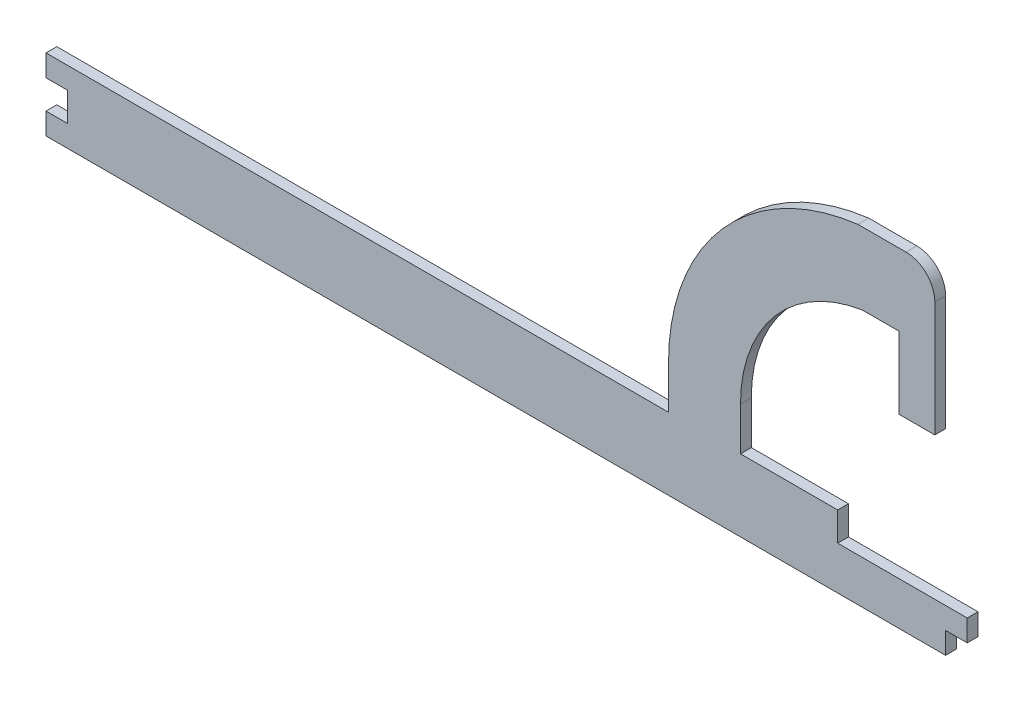
SolidWorks part; units mm, degrees
ref_plane "Спереди" through (0, 0, 0) normal (0, 0, 1) x (1, 0, 0)
ref_plane "Сверху" through (0, 0, 0) normal (0, 1, 0) x (1, 0, 0)
ref_plane "Справа" through (0, 0, 0) normal (1, 0, 0) x (0, 0, -1)
sketch "Эскиз2" plane through (0, 0, 0) normal (0, 0, 1) x (1, 0, 0)
  line L1 (0, 0) -> (244, 0)
  line L2 (0, 0) -> (0, 20) construction
  line L18 (244, 12) -> (244, 0) construction
  line L33 (0, 20) -> (167, 20)
  line L35 (187, 20) -> (187, 32)
  line L36 (187, 32) -> (167, 32) construction
  line L37 (167, 32) -> (167, 20)
  line L38 (231, 71.5474) -> (231, 51.5474)
  line L39 (231, 51.5474) -> (241, 51.5474)
  line L42 (187, 20) -> (214, 20)
  line L44 (241, 83.5474) -> (241, 51.5474)
  line L45 (231, 71.5474) -> (221, 71.5474)
  line L46 (233, 91.5474) -> (219.6446, 91.5474)
  line L47 (214, 20) -> (214, 12)
  line L48 (214, 12) -> (244, 12)
  line L49 (0, 20) -> (-6, 20)
  line L50 (-6, 20) -> (-6, 14)
  line L51 (-6, 14) -> (0, 14)
  line L52 (0, 14) -> (0, 6)
  line L53 (0, 6) -> (-6, 6)
  line L54 (-6, 6) -> (-6, 0)
  line L55 (-6, 0) -> (0, 0)
  line L56 (244, 12) -> (250, 12)
  line L57 (250, 12) -> (250, 6)
  line L58 (250, 6) -> (244, 6)
  line L59 (244, 6) -> (244, 0)
  arc A2 (241, 83.5474) -> (233, 91.5474) centre (233, 83.5474) ccw
  arc A7 (221, 71.5474) -> (187, 32) centre (227, 32) ccw
  arc A8 (219.6446, 91.5474) -> (167, 32) centre (227, 32) ccw
  dimension "D3" = 12
  dimension "D4" = 20
  dimension "D5" = 10
  dimension "D8" = 80
  dimension "D9" = 20
  dimension "D1" = 244
  dimension "D2" = 20
  dimension "D6" = 3
  dimension "D7" = 10
  dimension "D10" = 20
  dimension "D11" = 8
  dimension "D12" = 17
  dimension "D13" = 8
  dimension "D14" = 30
  dimension "D15" = 6
  dimension "D16" = 6
  dimension "D17" = 6
  dimension "D18" = 6
extrude "Бобышка-Вытянуть1" add sketch "Эскиз2" along normal blind 3
